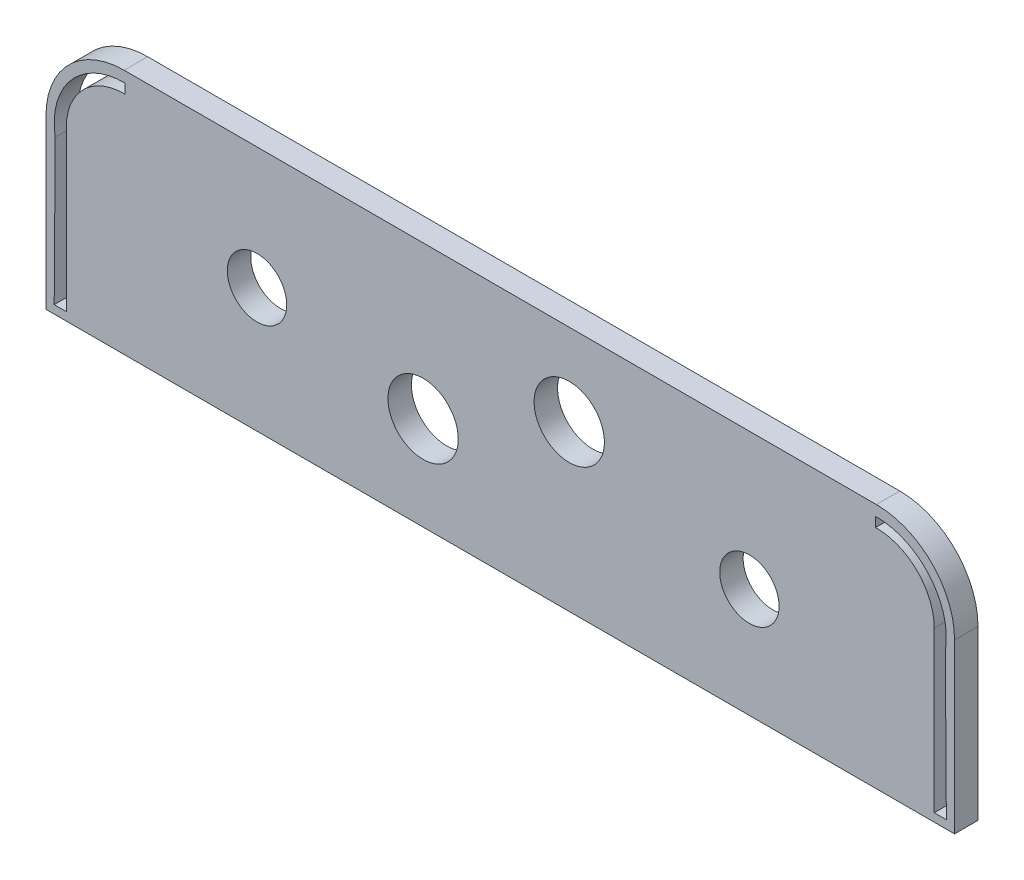
SolidWorks part; units mm, degrees
ref_plane "Front Plane" through (0, 0, 0) normal (0, 0, 1) x (1, 0, 0)
ref_plane "Top Plane" through (0, 0, 0) normal (0, 1, 0) x (1, 0, 0)
ref_plane "Right Plane" through (0, 0, 0) normal (1, 0, 0) x (0, 0, -1)
sketch "Sketch1" plane through (0, 0, 0) normal (0, 0, 1) x (1, 0, 0)
  line L0 (58.125, -1.75) -> (-58.125, -1.75) construction
  line L1 (-48.125, 15.75) -> (48.125, 15.75)
  line L2 (-58.125, 5.75) -> (-58.125, -15.75)
  line L3 (-58.125, -15.75) -> (58.125, -15.75)
  line L4 (58.125, 5.75) -> (58.125, -15.75)
  line L5 (-58.125, 15.75) -> (58.125, -15.75) construction
  line L6 (-58.125, -15.75) -> (58.125, 15.75) construction
  line L7 (31.875, 15.75) -> (31.875, -15.75) construction
  line L8 (-31.125, -15.75) -> (-31.125, 15.75) construction
  line L9 (-58.125, 0.15) -> (58.125, 0.15) construction
  line L10 (-76.0924, -14.25) -> (178.225, -14.25) construction
  arc A0 (48.125, 15.75) -> (58.125, 5.75) centre (48.125, 5.75) cw
  arc A1 (-48.125, 15.75) -> (-58.125, 5.75) centre (-48.125, 5.75) ccw
  circle A2 centre (31.875, -1.75) radius 3.8
  circle A3 centre (-31.125, 0.15) radius 3.8
  point P0 (0, 0)
  dimension "D3" = 10
  dimension "D6" = 7.6
  dimension "D8" = 27
  dimension "D1" = 116.25
  dimension "D2" = 31.5
  dimension "D4" = 14
  dimension "D5" = 26.25
  dimension "D7" = 120.4422
  dimension "D9" = 0
  dimension "D10" = 14.4
extrude "Boss-Extrude2" add sketch "Sketch1" along normal blind 3
sketch "Sketch2" plane through (0, 0, 3) normal (0, 0, 1) x (1, 0, 0)
  line L0 (-17.875, 15.75) -> (-17.875, -15.75) construction
  line L1 (48.125, 15.75) -> (-48.125, 15.75) construction
  line L2 (-58.125, -15.75) -> (58.125, -15.75) construction
  line L3 (21.625, 15.75) -> (21.625, -15.75) construction
  line L4 (-58.125, 5.25) -> (58.125, 5.25) construction
  line L5 (-58.125, 5.75) -> (-58.125, -15.75) construction
  line L6 (58.125, -15.75) -> (58.125, 5.75) construction
  line L7 (8.825, 15.75) -> (8.825, -15.75) construction
  line L8 (-9.875, 15.75) -> (-9.875, -15.75) construction
  line L9 (-58.125, -3.75) -> (58.125, -3.75) construction
  line L10 (0.675, 5.25) -> (0.675, -15.75) construction
  line L11 (-18.025, -3.75) -> (-18.025, -15.75) construction
  line L26 (55.625, -15.75) -> (55.625, 5.75)
  line L27 (55.625, -15.75) -> (55.625, 5.75)
  line L28 (-55.625, -15.75) -> (-58.125, -15.75)
  line L29 (-55.625, 5.75) -> (-55.625, -15.75)
  line L30 (-55.625, 5.75) -> (-55.625, -15.75)
  line L31 (-58.125, -15.75) -> (-58.125, 5.25)
  line L32 (-48.125, 13.25) -> (-48.125, 15.75)
  line L33 (55.625, -15.75) -> (58.125, -15.75)
  line L34 (58.125, -15.75) -> (58.125, 5.25)
  line L35 (48.125, 13.25) -> (48.125, 15.75)
  circle A0 centre (-31.125, 0.15) radius 13.25 construction
  circle A1 centre (31.875, -1.75) radius 10.25 construction
  circle A2 centre (8.825, 5.25) radius 18 construction
  circle A3 centre (8.825, 5.25) radius 4.35
  circle A4 centre (8.825, 5.25) radius 8.15 construction
  circle A5 centre (-9.875, -3.75) radius 8.15 construction
  circle A6 centre (-9.875, -3.75) radius 4.35
  arc A10 (58.125, 5.75) -> (48.125, 15.75) centre (48.125, 5.75) ccw
  arc A11 (58.125, 5.75) -> (48.125, 15.75) centre (48.125, 5.75) ccw
  arc A13 (-48.125, 15.75) -> (-58.125, 5.75) centre (-48.125, 5.75) ccw
  arc A14 (-48.125, 15.75) -> (-58.125, 5.75) centre (-48.125, 5.75) ccw
  arc A28 (55.625, 5.75) -> (48.125, 13.25) centre (48.125, 5.75) ccw
  arc A29 (55.625, 5.75) -> (48.125, 13.25) centre (48.125, 5.75) ccw
  arc A32 (-48.125, 13.25) -> (-55.625, 5.75) centre (-48.125, 5.75) ccw
  arc A33 (-48.125, 13.25) -> (-55.625, 5.75) centre (-48.125, 5.75) ccw
  line M2 (58.125, -15.75) -> (58.125, 5.75)
  arc M3 (58.125, 5.75) -> (48.125, 15.75) centre (48.125, 5.75) ccw
  arc M5 (-48.125, 15.75) -> (-58.125, 5.75) centre (-48.125, 5.75) ccw
  line M6 (-58.125, 5.75) -> (-58.125, -15.75)
  line M7 (-58.125, -15.75) -> (58.125, -15.75)
  dimension "D1" = 26.5
  dimension "D2" = 20.5
  dimension "D6" = 8.7
  dimension "D8" = 10.55
  dimension "D9" = 8.7
  dimension "D10" = 18.55
  dimension "D7" = 31.5
  dimension "D11" = 12
  dimension "16" = 16.3
  dimension "D12" = 16.3
  dimension "D13" = 36
  dimension "D14" = 8
  dimension "D16" = 2.5
  dimension "D3" = 39.5
  dimension "D4" = 12.8
  dimension "D15" = 0.15
  dimension "D20" = 21
  dimension "D17" = 2.5
  dimension "D18" = 0
  dimension "D19" = 0
other "AlignGroup1"
other "AlignGroup2"
other "AlignGroup3"
other "AlignGroup4"
other "AlignGroup5"
extrude "Boss-Extrude3" add sketch "Sketch2" along normal blind 25 contours A3 | A6 | A29 L27 L35 M7 M2 M3 | A33 L32 L30 M5 M6 M7
sketch "Sketch5" plane through (0, 0, 28) normal (0, 0, 1) x (1, 0, 0)
  line L0 (55.525, -14.7) -> (55.525, 5.75)
  line L1 (48.025, 13.1493) -> (48.025, 14.3846)
  line L2 (56.9469, 3.9266) -> (57.0757, -14.7)
  line L3 (55.525, -14.7) -> (57.0757, -14.7)
  line L5 (0, 15.75) -> (0, -15.75) construction
  line L6 (48.125, 15.75) -> (-48.125, 15.75) construction
  line L7 (-55.625, -15.75) -> (55.625, -15.75) construction
  line L20 (-56.9469, 3.9266) -> (-57.0757, -14.7)
  line L22 (-55.525, -14.7) -> (-57.0757, -14.7)
  line L36 (-55.525, -14.7) -> (-55.525, 5.75)
  line L37 (-48.025, 13.1493) -> (-48.025, 14.3846)
  arc A0 (48.025, 13.1493) -> (55.525, 5.75) centre (48.125, 5.75) cw
  arc A1 (48.025, 14.3846) -> (56.9469, 3.9266) centre (48.125, 5.4352) cw
  arc A8 (-48.025, 14.3846) -> (-56.9469, 3.9266) centre (-48.125, 5.4352) ccw
  arc A9 (-48.025, 13.1493) -> (-55.525, 5.75) centre (-48.125, 5.75) ccw
sketch "Sketch10" plane through (0, 0, 28) normal (0, 0, 1) x (1, 0, 0)
  circle A1 centre (8.825, 5.25) radius 4.35
  circle A2 centre (8.825, 5.25) radius 4.35
  circle A3 centre (-9.875, -3.75) radius 4.35
  circle A4 centre (-9.875, -3.75) radius 4.35
  dimension "D1" = 0
  dimension "D2" = 0
extrude "Cut-Extrude3" cut sketch "Sketch10" against normal blind 1
extrude "Cut-Extrude4" cut sketch "Sketch5" against normal blind 50
sketch "Sketch12" plane through (0, 0, 27) normal (0, 0, 1) x (1, 0, 0)
  circle A3 centre (-9.875, -3.75) radius 4.5
  circle A5 centre (-9.875, -3.75) radius 4.5
  circle A7 centre (8.825, 5.25) radius 4.5
  circle A8 centre (8.825, 5.25) radius 4.5
  dimension "D1" = 0.15
  dimension "D2" = 0.15
extrude "Cut-Extrude6" cut sketch "Sketch12" against normal blind 50
sketch "Sketch13" plane through (0, 0, 28) normal (0, 0, 1) x (1, 0, 0)
  line L0 (57.0757, -14.7) -> (55.625, -14.7) construction
  line L1 (55.625, -14.7) -> (55.625, -15.75) construction
  line L2 (55.625, -15.75) -> (58.125, -15.75) construction
  line L3 (58.125, -15.75) -> (58.125, 5.75) construction
  line L4 (48.125, 15.75) -> (48.125, 14.3852) construction
  line L5 (56.9469, 3.9266) -> (57.0757, -14.7) construction
  line L6 (-48.125, 14.3852) -> (-48.125, 15.75) construction
  line L7 (-58.125, 5.75) -> (-58.125, -15.75) construction
  line L8 (-58.125, -15.75) -> (-55.625, -15.75) construction
  line L9 (-55.625, -15.75) -> (-55.625, -14.7) construction
  line L10 (-55.625, -14.7) -> (-57.0757, -14.7) construction
  line L11 (-57.0757, -14.7) -> (-56.9469, 3.9266) construction
  line L12 (57.0757, -14.7) -> (55.625, -14.7)
  line L13 (55.625, -14.7) -> (55.625, -15.75)
  line L14 (55.625, -15.75) -> (58.125, -15.75)
  line L15 (58.125, -15.75) -> (58.125, 5.75)
  line L16 (48.125, 15.75) -> (48.125, 14.3852)
  line L17 (56.9469, 3.9266) -> (57.0757, -14.7)
  line L18 (-48.125, 14.3852) -> (-48.125, 15.75)
  line L19 (-58.125, 5.75) -> (-58.125, -15.75)
  line L20 (-58.125, -15.75) -> (-55.625, -15.75)
  line L21 (-55.625, -15.75) -> (-55.625, -14.7)
  line L22 (-55.625, -14.7) -> (-57.0757, -14.7)
  line L23 (-57.0757, -14.7) -> (-56.9469, 3.9266)
  arc A0 (58.125, 5.75) -> (48.125, 15.75) centre (48.125, 5.75) ccw construction
  arc A1 (56.9469, 3.9266) -> (48.125, 14.3852) centre (48.125, 5.4352) ccw construction
  arc A2 (-48.125, 14.3852) -> (-56.9469, 3.9266) centre (-48.125, 5.4352) ccw construction
  arc A3 (-48.125, 15.75) -> (-58.125, 5.75) centre (-48.125, 5.75) ccw construction
  arc A4 (58.125, 5.75) -> (48.125, 15.75) centre (48.125, 5.75) ccw
  arc A5 (56.9469, 3.9266) -> (48.125, 14.3852) centre (48.125, 5.4352) ccw
  arc A6 (-48.125, 14.3852) -> (-56.9469, 3.9266) centre (-48.125, 5.4352) ccw
  arc A7 (-48.125, 15.75) -> (-58.125, 5.75) centre (-48.125, 5.75) ccw
extrude "Cut-Extrude7" cut sketch "Sketch13" against normal up to surface (25 mm away) up to face at (-5.375, -3.75, 3)
